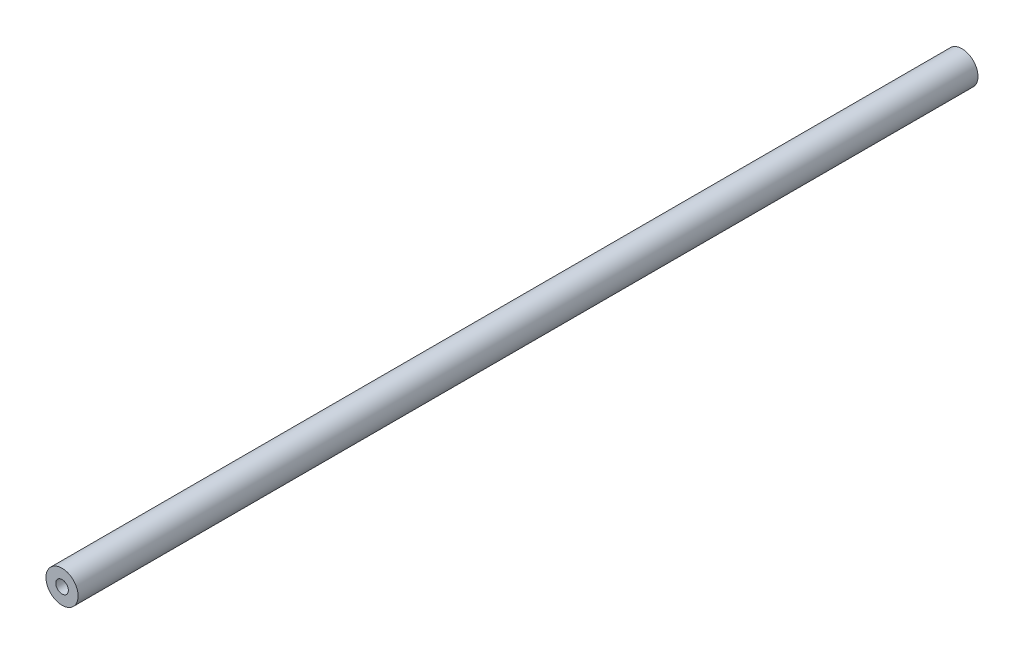
SolidWorks part; units mm, degrees
material "6061-T6 (SS)"
ref_plane "Front Plane" through (0, 0, 0) normal (0, 0, 1) x (1, 0, 0)
ref_plane "Top Plane" through (0, 0, 0) normal (0, 1, 0) x (1, 0, 0)
ref_plane "Right Plane" through (0, 0, 0) normal (1, 0, 0) x (0, 0, -1)
sketch "Sketch1" plane through (0, 0, 0) normal (0, 0, 1) x (1, 0, 0)
  circle A0 centre (0, 0) radius 6.35
  dimension "D1" = 12.7
extrude "Boss-Extrude1" add sketch "Sketch1" along normal mid plane 355.6
sketch "Sketch3" plane through (0, 0, 177.8) normal (0, 0, 1) x (1, 0, 0)
  circle A0 centre (0, 0) radius 2.4892
  dimension "D1" = 4.9784
extrude "Cut-Extrude1" cut sketch "Sketch3" against normal blind 19.05
mirror "Mirror1" about plane through (0, 0, 0) normal (0, 0, 1) of "Cut-Extrude1"
